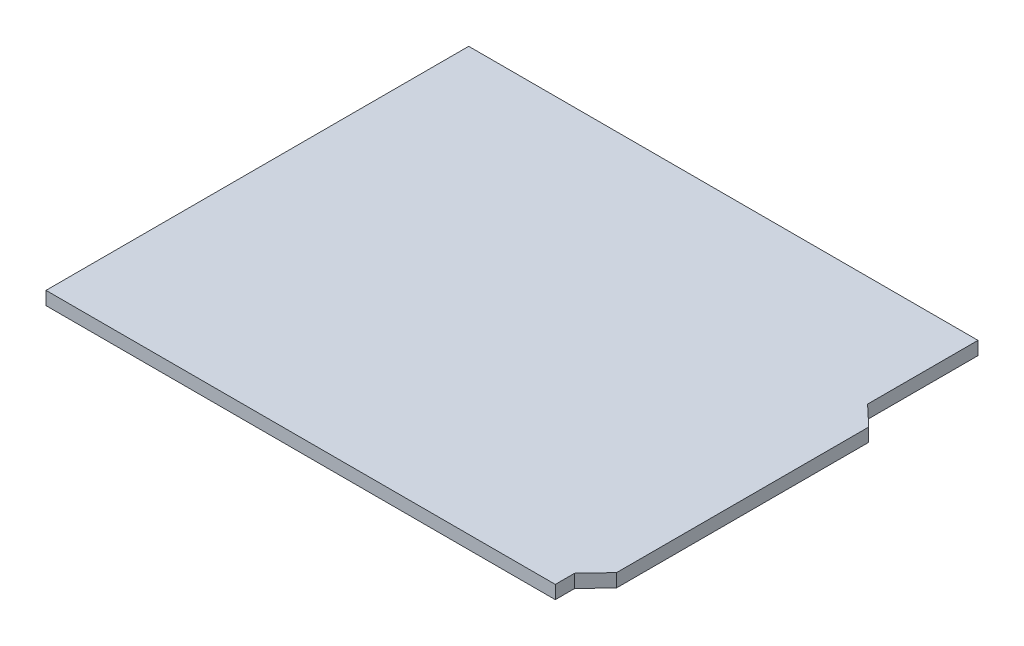
SolidWorks part; units mm, degrees
ref_plane "Alzado" through (0, 0, 0) normal (0, 0, 1) x (1, 0, 0)
ref_plane "Planta" through (0, 0, 0) normal (0, 1, 0) x (1, 0, 0)
ref_plane "Vista lateral" through (0, 0, 0) normal (1, 0, 0) x (0, 0, -1)
sketch "Croquis1" plane through (0, 0, 0) normal (0, 1, 0) x (1, 0, 0)
  line L0 (33.025, 13.09) -> (35.675, 10.59)
  line L1 (-33.025, -27.41) -> (33.025, -27.41)
  line L2 (-33.025, -27.41) -> (-33.025, 27.41)
  line L3 (-33.025, 27.41) -> (33.025, 27.41)
  line L4 (33.025, -27.41) -> (33.025, 27.41)
  line L5 (-33.025, -27.41) -> (33.025, 27.41) construction
  line L6 (-33.025, 27.41) -> (33.025, -27.41) construction
  line L7 (35.675, 10.59) -> (35.675, -22.11)
  line L8 (35.675, -22.11) -> (33.025, -24.91)
  point P0 (0, 0)
  dimension "D1" = 66.05
  dimension "D2" = 54.82
  dimension "D3" = 68.7
  dimension "D4" = 2.5
  dimension "D5" = 5.3
  dimension "D6" = 32.7
  dimension "D7" = 38
extrude "Saliente-Extruir1" add sketch "Croquis1" along normal blind 1.72 contours L1 L4 L3 L2 | L8 L7 L0 L4
